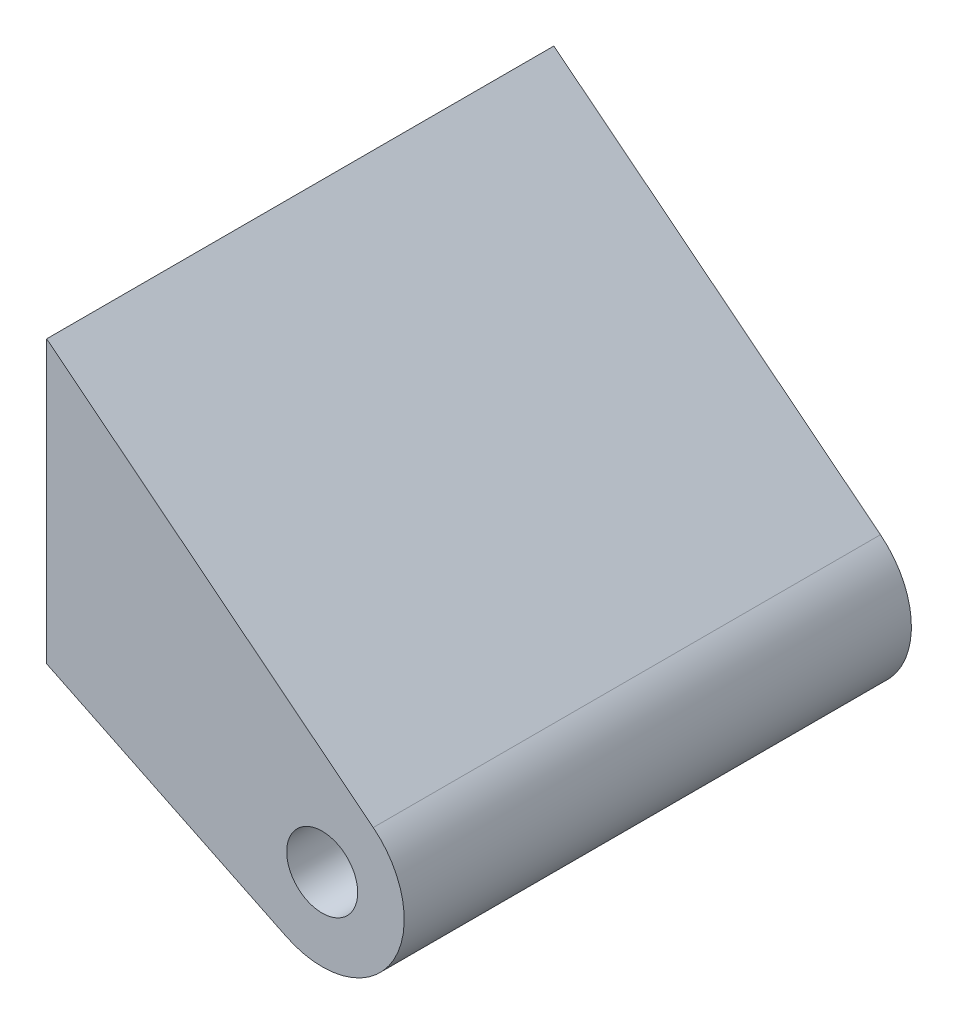
SolidWorks part; units mm, degrees
ref_plane "Front Plane" through (0, 0, 0) normal (0, 0, 1) x (1, 0, 0)
ref_plane "Top Plane" through (0, 0, 0) normal (0, 1, 0) x (1, 0, 0)
ref_plane "Right Plane" through (0, 0, 0) normal (1, 0, 0) x (0, 0, -1)
sketch "Sketch1" plane through (0, 0, 0) normal (0, 0, 1) x (1, 0, 0)
  line L0 (-32.198, 25.6221) -> (0, 0)
  line L1 (-32.198, 25.6221) -> (-32.198, -2.1201)
  line L2 (-32.198, -2.1201) -> (-8.5648, -13.597)
  arc A0 (0, 0) -> (-8.5648, -13.597) centre (-5.0335, -6.3254) cw
  circle A1 centre (-5.0335, -6.3254) radius 3.5
  dimension "D1" = 7
extrude "Boss-Extrude1" add sketch "Sketch1" along normal blind 50
